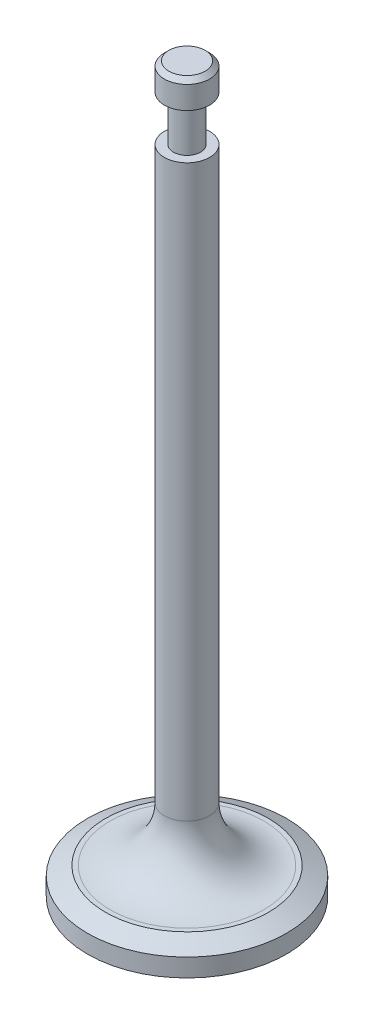
SolidWorks part; units mm, degrees
material "Brass"
ref_plane "Front Plane" through (0, 0, 0) normal (0, 0, 1) x (1, 0, 0)
ref_plane "Top Plane" through (0, 0, 0) normal (0, 1, 0) x (1, 0, 0)
ref_plane "Right Plane" through (0, 0, 0) normal (1, 0, 0) x (0, 0, -1)
sketch "Sketch1" plane through (0, 0, 0) normal (1, 0, 0) x (0, 0, -1)
  line L0 (0, 0) -> (0, -320)
  line L1 (0, -320) -> (44, -320)
  line L2 (44, -320) -> (44, -308)
  line L3 (44, -308) -> (10, -308)
  line L4 (10, -308) -> (10, -32)
  line L5 (10, -32) -> (6, -32)
  line L6 (6, -32) -> (6, -12)
  line L7 (6, -12) -> (10, -12)
  line L8 (10, -12) -> (10, 0)
  line L9 (10, 0) -> (0, 0)
  dimension "D1" = 320
  dimension "D2" = 44
  dimension "D3" = 12
  dimension "D4" = 10
  dimension "D5" = 12
  dimension "D6" = 20
  dimension "D7" = 4
revolve "Revolve1" add sketch "Sketch1" angle 360 about L0
fillet "Fillet1" radius 24 1 edges at (0, -308, 10)
chamfer "Chamfer1" distance 4 distance2 8 1 edges at (0, -308, 44)
chamfer "Chamfer2" distance 2 angle 45 1 edges at (0, 0, 10)
